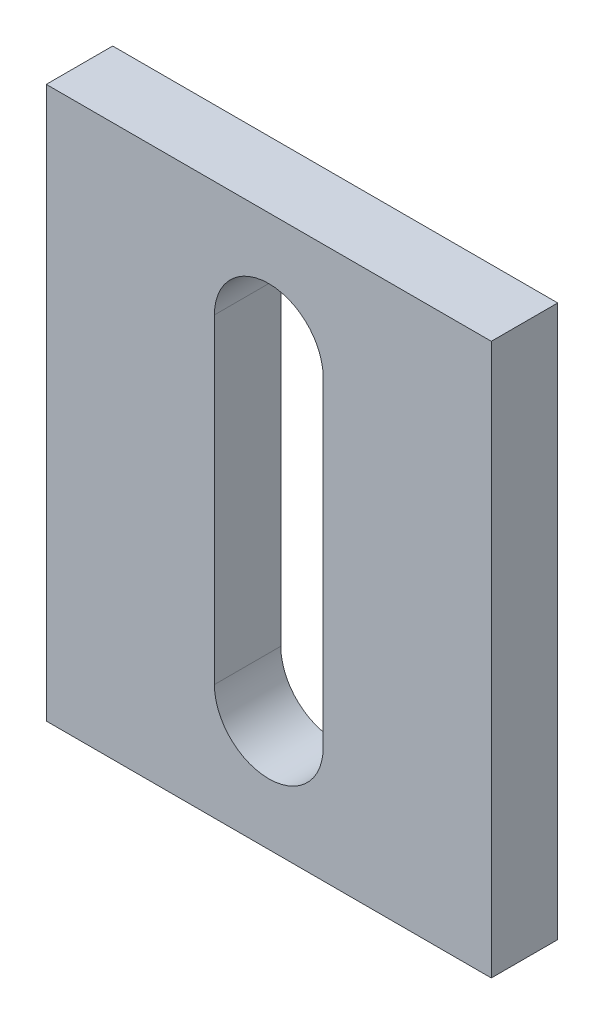
SolidWorks part; units mm, degrees
ref_plane "前视基准面" through (0, 0, 0) normal (0, 0, 1) x (1, 0, 0)
ref_plane "上视基准面" through (0, 0, 0) normal (0, 1, 0) x (1, 0, 0)
ref_plane "右视基准面" through (0, 0, 0) normal (1, 0, 0) x (0, 0, -1)
sketch "草图1" plane through (0, 0, 0) normal (0, 0, 1) x (1, 0, 0)
  line L0 (0, 0) -> (3, 0)
  line L1 (0, 0) -> (35, 0) construction
  line L2 (0, 0) -> (0, -40) construction
  line L3 (0, -40) -> (35, -40) construction
  line L4 (35, 0) -> (35, -40) construction
  line L5 (35, 0) -> (32, 0)
  line L6 (0, -40) -> (0, -35.7)
  line L7 (0, -35.7) -> (63.6248, -35.7) construction
  line L8 (3, 0) -> (31.8124, -35.7) construction
  line L9 (3, 0) -> (31.8124, 0)
  line L10 (3, 0) -> (3, -35.7)
  line L11 (3, -35.7) -> (31.8124, -35.7)
  line L12 (31.8124, 0) -> (31.8124, -35.7)
  line L13 (17.4062, -7.4876) -> (17.4062, -28.2124) construction
  line L14 (20.9284, -7.4876) -> (20.9284, -28.2124)
  line L15 (13.884, -7.4876) -> (13.884, -28.2124)
  arc A0 (20.9284, -7.4876) -> (13.884, -7.4876) centre (17.4062, -7.4876) ccw
  arc A1 (13.884, -28.2124) -> (20.9284, -28.2124) centre (17.4062, -28.2124) ccw
  point P14 (17.4062, -17.85)
extrude "凸台-拉伸1" add sketch "草图1" along normal blind 4.3 contours L12 L9 L10 L11 A1 L15 A0 L14
